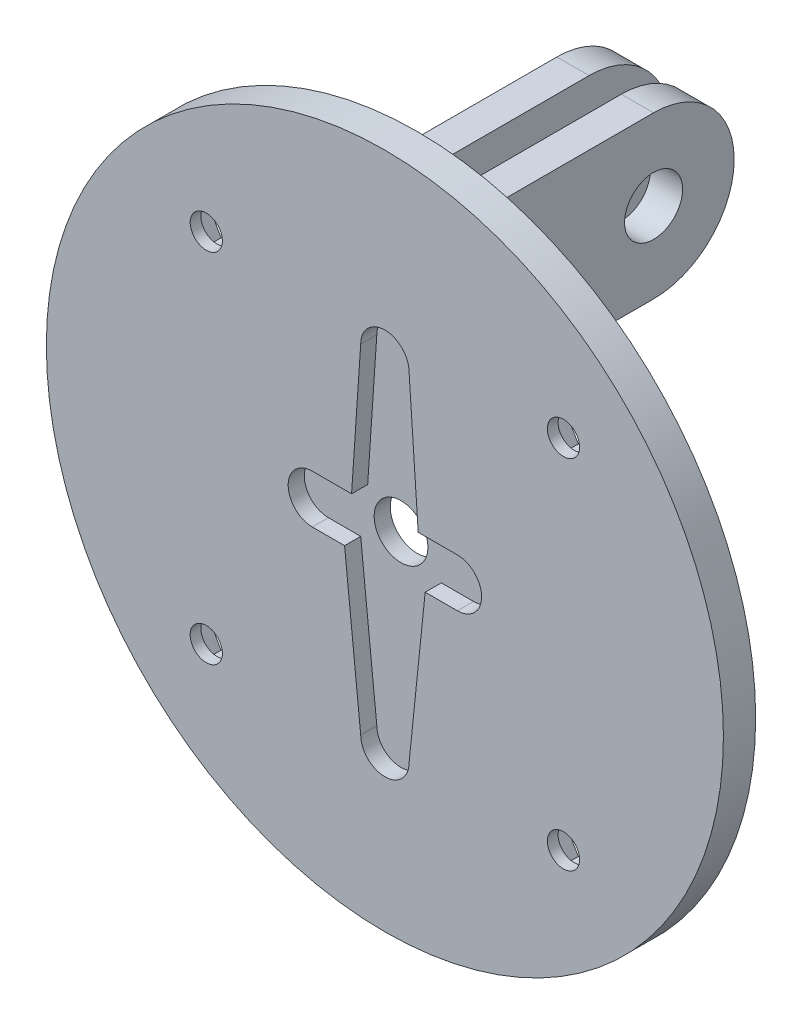
SolidWorks part; units mm, degrees
ref_plane "Alzado" through (0, 0, 0) normal (0, 0, 1) x (1, 0, 0)
ref_plane "Planta" through (0, 0, 0) normal (0, 1, 0) x (1, 0, 0)
ref_plane "Vista lateral" through (0, 0, 0) normal (1, 0, 0) x (0, 0, -1)
sketch "Croquis1" plane through (0, 0, 0) normal (0, 0, 1) x (1, 0, 0)
  line L1 (-21.1753, 30.481) -> (-65.7231, 30.481) construction
  line L3 (-65.7231, -14.0668) -> (-21.1753, -14.0668) construction
  line L4 (-21.1753, -14.0668) -> (-21.1753, 30.481) construction
  line L5 (-21.1753, 30.481) -> (-65.7231, -14.0668) construction
  line L6 (-65.7231, -14.0668) -> (-65.7231, 30.481) construction
  line L7 (-65.7231, 30.481) -> (-21.1753, -14.0668) construction
  circle A0 centre (-43.4492, 8.2071) radius 31.5
  circle A2 centre (-60.0662, 24.8241) radius 1.5
  circle A3 centre (-26.8322, 24.8241) radius 1.5
  circle A4 centre (-26.8322, -8.4099) radius 1.5
  circle A5 centre (-60.0662, -8.4099) radius 1.5
  dimension "D1" = 63
  dimension "D3" = 8
  dimension "D4" = 8
  dimension "D5" = 8
  dimension "D6" = 8
extrude "Saliente-Extruir1" add sketch "Croquis1" along normal blind 3
sketch "Croquis3" plane through (0, 0, 3) normal (0, 0, 1) x (1, 0, 0)
  line L0 (-43.4492, 8.2071) -> (-34.4492, 8.2071) construction
  line L1 (-43.4492, 8.2071) -> (-43.4492, -10.7929) construction
  line L2 (-43.4492, 8.2071) -> (-43.4492, 25.2071) construction
  line L3 (-43.4492, 8.2071) -> (-52.4492, 8.2071) construction
  line L4 (-43.4492, 8.2071) -> (-43.4492, 10.4571) construction
  line L5 (-52.4492, 8.2071) -> (-50.1992, 8.2071) construction
  line L6 (-43.4492, 10.4571) -> (-40.3492, 10.4571) construction
  line L7 (-43.4492, 10.4571) -> (-46.5492, 10.4571) construction
  line L10 (-43.4492, 25.2071) -> (-43.4492, 22.9571) construction
  line L11 (-43.4492, 22.9571) -> (-41.1992, 22.9571) construction
  line L13 (-43.4492, 22.9571) -> (-45.6992, 22.9571) construction
  line L15 (-41.1992, 22.9571) -> (-40.3492, 10.4571)
  line L16 (-45.6992, 22.9571) -> (-46.5492, 10.4571)
  line L17 (-43.4492, 8.2071) -> (-43.4492, 5.9571) construction
  line L18 (-43.4492, 5.9571) -> (-39.6992, 5.9571) construction
  line L19 (-43.4492, 5.9571) -> (-47.1992, 5.9571) construction
  line L22 (-43.4492, -10.7929) -> (-43.4492, -8.5429) construction
  line L23 (-43.4492, -8.5429) -> (-41.1992, -8.5429) construction
  line L25 (-43.4492, -8.5429) -> (-45.6992, -8.5429) construction
  line L26 (-47.1992, 5.9571) -> (-45.6992, -8.5429)
  line L27 (-39.6992, 5.9571) -> (-41.1992, -8.5429)
  line L28 (-46.5492, 10.4571) -> (-50.1992, 10.4571)
  line L29 (-47.1992, 5.9571) -> (-50.1992, 5.9571)
  line L30 (-34.4492, 8.2071) -> (-36.6992, 8.2071) construction
  line L31 (-40.3492, 10.4571) -> (-36.6992, 10.4571)
  line L32 (-39.6992, 5.9571) -> (-36.6992, 5.9571)
  arc A0 (-45.6992, 22.9571) -> (-41.1992, 22.9571) centre (-43.4492, 22.9571) cw
  arc A1 (-45.6992, -8.5429) -> (-41.1992, -8.5429) centre (-43.4492, -8.5429) ccw
  arc A2 (-50.1992, 5.9571) -> (-50.1992, 10.4571) centre (-50.1992, 8.2071) cw
  arc A3 (-36.6992, 10.4571) -> (-36.6992, 5.9571) centre (-36.6992, 8.2071) cw
  dimension "D1" = 17
  dimension "D2" = 19
  dimension "D3" = 9
  dimension "D4" = 9
  dimension "D5" = 2.25
  dimension "D6" = 2.25
extrude "Cortar-Extruir2" cut sketch "Croquis3" against normal blind 1.5
sketch "Croquis4" plane through (0, 0, 0) normal (0, 0, -1) x (-1, 0, 0)
  circle A0 centre (43.4492, 8.2071) radius 2.5
  dimension "D1" = 5
extrude "Cortar-Extruir3" cut sketch "Croquis4" against normal blind 3
sketch "Croquis5" plane through (0, 0, 0) normal (0, 0, -1) x (-1, 0, 0)
  line L0 (43.4492, 8.2071) -> (43.4492, 39.7071) construction
  line L1 (43.4492, 34.7071) -> (47.9492, 34.7071) construction
  line L2 (47.9492, 34.7071) -> (47.9492, 19.7071) construction
  line L3 (41.9492, 19.7071) -> (41.9492, 34.7071)
  line L5 (47.9492, 34.7071) -> (47.9492, 19.7071)
  line L7 (38.9492, 34.7071) -> (38.9492, 19.7071)
  line L8 (44.9492, 19.7071) -> (44.9492, 34.7071)
  line L9 (44.9492, 19.7071) -> (47.9492, 19.7071)
  line L10 (38.9492, 19.7071) -> (41.9492, 19.7071)
  line L11 (38.9492, 34.7071) -> (41.9492, 34.7071)
  line L12 (44.9492, 34.7071) -> (47.9492, 34.7071)
  circle A0 centre (43.4492, 8.2071) radius 31.5 construction
  dimension "D1" = 5
  dimension "D2" = 4.5
  dimension "D3" = 15
  dimension "D4" = 9
  dimension "D5" = 3
  dimension "D6" = 3
extrude "Saliente-Extruir2" add sketch "Croquis5" along normal blind 25
sketch "Croquis6" plane through (-38.9492, 0, 0) normal (1, 0, 0) x (0, 0, -1)
  line L0 (25, 34.7071) -> (17.5, 34.7071) construction
  line L1 (25, 34.7071) -> (0, 34.7071) construction
  line L2 (17.5, 34.7071) -> (17.5, 27.2071) construction
  line L3 (17.5, 27.2071) -> (17.5, 19.7071) construction
  line L4 (25, 19.7071) -> (0, 19.7071) construction
  line L5 (17.5, 34.7071) -> (25, 34.7071)
  line L6 (25, 34.7071) -> (25, 19.7071)
  line L7 (25, 19.7071) -> (17.5, 19.7071)
  arc A0 (17.5, 34.7071) -> (17.5, 19.7071) centre (17.5, 27.2071) cw
  circle A1 centre (17.5, 27.2071) radius 2.7
  line M2 (0, 19.7071) -> (25, 19.7071)
  line M3 (25, 19.7071) -> (25, 34.7071)
  line M4 (25, 34.7071) -> (0, 34.7071)
  dimension "D1" = 5.4
extrude "Cortar-Extruir4" cut sketch "Croquis6" against normal up to vertex contours A0 L6 M4 | A0 M3 M2 | A1
sketch "Croquis7" plane through (0, 0, 0) normal (0, 0, -1) x (-1, 0, 0)
  line L1 (30.0653, 24.8241) -> (28.4488, 27.6241)
  line L2 (28.4488, 27.6241) -> (25.2156, 27.6241)
  line L3 (25.2156, 27.6241) -> (23.599, 24.8241)
  line L4 (23.599, 24.8241) -> (25.2156, 22.0241)
  line L5 (25.2156, 22.0241) -> (28.4488, 22.0241)
  line L6 (28.4488, 22.0241) -> (30.0653, 24.8241)
  line L7 (63.2994, 24.8241) -> (61.6828, 27.6241)
  line L8 (61.6828, 27.6241) -> (58.4496, 27.6241)
  line L9 (58.4496, 27.6241) -> (56.833, 24.8241)
  line L10 (56.833, 24.8241) -> (58.4496, 22.0241)
  line L11 (58.4496, 22.0241) -> (61.6828, 22.0241)
  line L12 (61.6828, 22.0241) -> (63.2994, 24.8241)
  line L13 (30.0653, -8.4099) -> (28.4488, -5.6099)
  line L14 (28.4488, -5.6099) -> (25.2156, -5.6099)
  line L15 (25.2156, -5.6099) -> (23.599, -8.4099)
  line L16 (23.599, -8.4099) -> (25.2156, -11.2099)
  line L17 (25.2156, -11.2099) -> (28.4488, -11.2099)
  line L18 (28.4488, -11.2099) -> (30.0653, -8.4099)
  line L19 (56.833, -8.4099) -> (58.4496, -11.2099)
  line L20 (58.4496, -11.2099) -> (61.6828, -11.2099)
  line L21 (61.6828, -11.2099) -> (63.2994, -8.4099)
  line L22 (63.2994, -8.4099) -> (61.6828, -5.6099)
  line L23 (61.6828, -5.6099) -> (58.4496, -5.6099)
  line L24 (58.4496, -5.6099) -> (56.833, -8.4099)
  circle A0 centre (26.8322, 24.8241) radius 2.8 construction
  circle A2 centre (60.0662, 24.8241) radius 2.8 construction
  circle A3 centre (26.8322, -8.4099) radius 2.8 construction
  circle A4 centre (60.0662, -8.4099) radius 2.8 construction
  dimension "D1" = 5.6
  dimension "D2" = 5.6
extrude "Cortar-Extruir5" cut sketch "Croquis7" against normal blind 2
